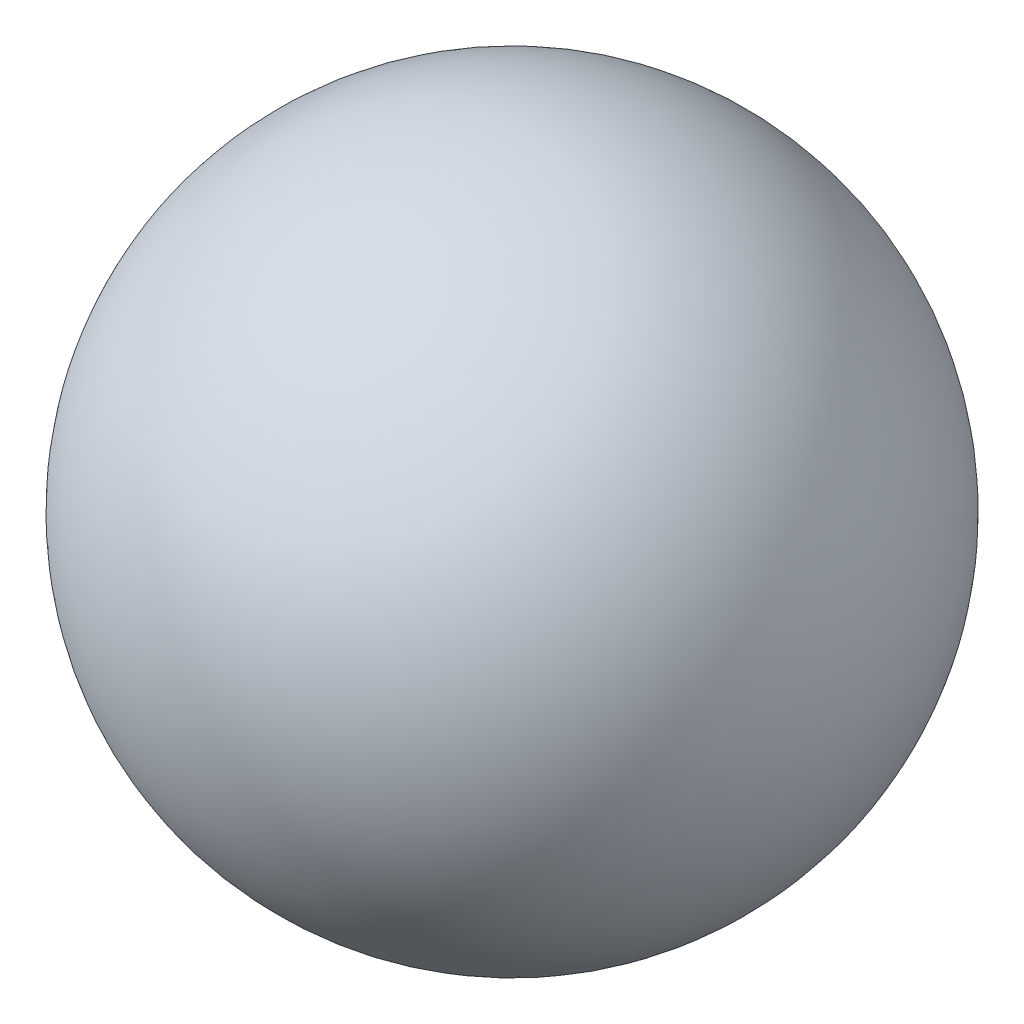
SolidWorks part; units mm, degrees
material "Nikel"
ref_plane "Ön Düzlem" through (0, 0, 0) normal (0, 0, 1) x (1, 0, 0)
ref_plane "Üst Düzlem" through (0, 0, 0) normal (0, 1, 0) x (1, 0, 0)
ref_plane "Sağ Düzlem" through (0, 0, 0) normal (1, 0, 0) x (0, 0, -1)
sketch "Çizim1" plane through (0, 0, 0) normal (0, 0, 1) x (1, 0, 0)
  line L0 (2.8, 0) -> (-2.8, 0) construction
  line L1 (2.8, 0) -> (-2.8, 0)
  arc A0 (-2.8, 0) -> (2.8, 0) centre (0, 0) ccw
  dimension "D1" = 2.8
revolve "Döndür1" add sketch "Çizim1" angle 360 about L0
